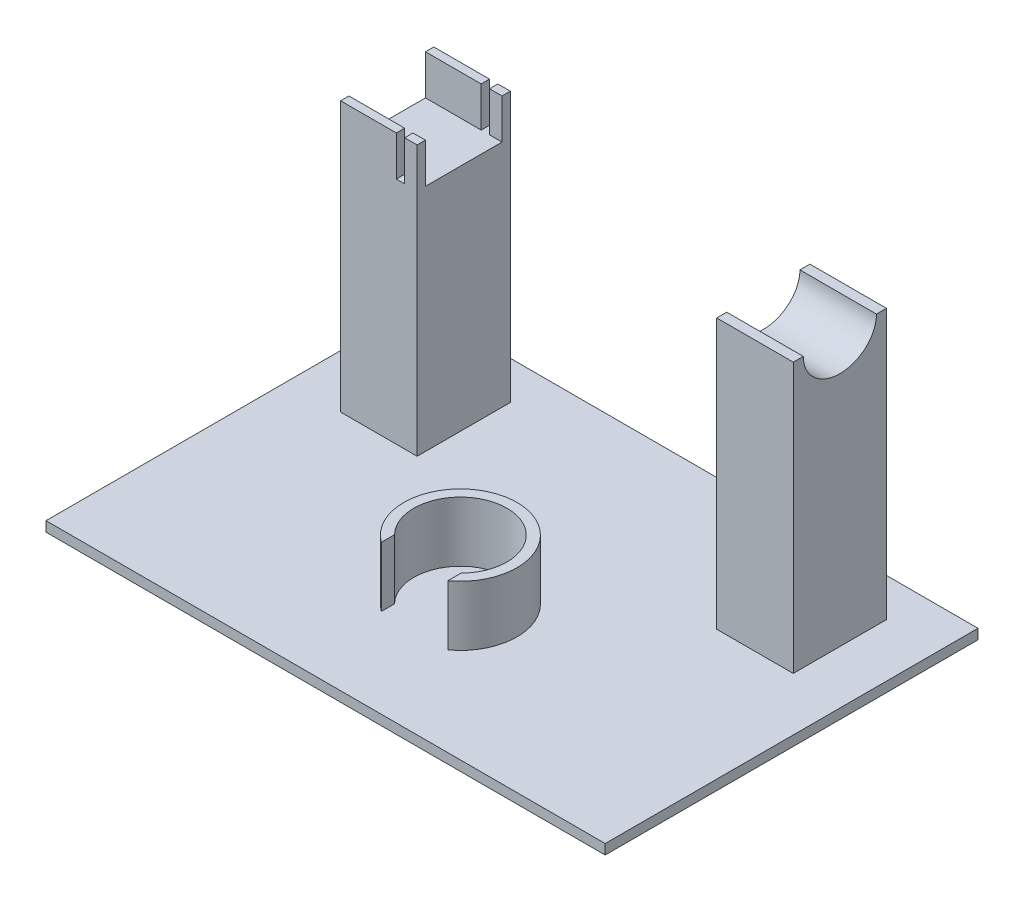
SolidWorks part; units mm, degrees
ref_plane "Front Plane" through (0, 0, 0) normal (0, 0, 1) x (1, 0, 0)
ref_plane "Top Plane" through (0, 0, 0) normal (0, 1, 0) x (1, 0, 0)
ref_plane "Right Plane" through (0, 0, 0) normal (1, 0, 0) x (0, 0, -1)
sketch "Sketch1" plane through (0, 0, 0) normal (0, 1, 0) x (1, 0, 0)
  line L1 (-84, 56) -> (84, 56)
  line L2 (-84, 56) -> (-84, -56)
  line L3 (-84, -56) -> (84, -56)
  line L4 (84, 56) -> (84, -56)
  line L5 (-84, 56) -> (84, -56) construction
  line L6 (-84, -56) -> (84, 56) construction
  point P0 (0, 0)
  dimension "D1" = 168
  dimension "D2" = 112
extrude "Boss-Extrude1" add sketch "Sketch1" along normal blind 3 contours L2 L3 L4 L1
sketch "Sketch2" plane through (0, 3, 0) normal (0, 1, 0) x (1, 0, 0)
  line L1 (-68, 44.5) -> (68, 44.5)
  line L2 (-68, 44.5) -> (-68, -44.5)
  line L3 (-68, -44.5) -> (68, -44.5)
  line L4 (68, 44.5) -> (68, -44.5)
  line L5 (-68, 44.5) -> (68, -44.5) construction
  line L6 (-68, -44.5) -> (68, 44.5) construction
  line L8 (-68, 44.5) -> (-45, 44.5)
  line L9 (-68, 44.5) -> (-68, 16.5)
  line L10 (-68, 16.5) -> (-45, 16.5)
  line L11 (-45, 44.5) -> (-45, 16.5)
  point P0 (0, 0)
  dimension "D1" = 136
  dimension "D2" = 89
  dimension "D3" = 28
  dimension "D4" = 23
extrude "Boss-Extrude2" add sketch "Sketch2" along normal blind 81 contours L8 L11 L10 L9
mirror "Mirror1" about plane through (0, 0, 0) normal (1, 0, 0) of "Boss-Extrude2"
sketch "Sketch11" plane through (0, 84, 0) normal (0, 1, 0) x (1, 0, 0)
  line L1 (-45, 16.5) -> (-45, 44.5)
  line L4 (-73, 42) -> (-45, 42)
  line L5 (-73, 42) -> (-73, 19)
  line L6 (-73, 19) -> (-45, 19)
  line L7 (-45, 42) -> (-45, 19)
  line L8 (-73, 42) -> (-45, 19) construction
  line L9 (-73, 19) -> (-45, 42) construction
  point P4 (-59, 30.5)
  dimension "D1" = 23
  dimension "D2" = 28
extrude "Cut-Extrude4" cut sketch "Sketch11" against normal blind 12 contours L4 L7 L6 L5
sketch "Sketch13" plane through (0, 72, 0) normal (0, 1, 0) x (1, 0, 0)
  line L3 (-51.25, 47.3449) -> (-48.75, 47.3449)
  line L4 (-51.25, 47.3449) -> (-51.25, 13.6551)
  line L5 (-51.25, 13.6551) -> (-48.75, 13.6551)
  line L6 (-48.75, 47.3449) -> (-48.75, 13.6551)
  line L7 (-51.25, 47.3449) -> (-48.75, 13.6551) construction
  line L8 (-51.25, 13.6551) -> (-48.75, 47.3449) construction
  dimension "D2" = 2.5
extrude "Cut-Extrude5" cut sketch "Sketch13" along normal blind 12 contours L4 L5 L6 L3
sketch "Sketch17" plane through (45, 0, 0) normal (-1, 0, 0) x (0, 0, 1)
  line L0 (-44.5, 84) -> (-16.5, 84) construction
  ellipse E0 centre (-30.5, 84) end of major axis (-19.5, 84) minor radius 10
extrude "Cut-Extrude6" cut sketch "Sketch17" against normal blind 40
sketch "Sketch18" plane through (0, 3, 0) normal (0, 1, 0) x (1, 0, 0)
  circle A0 centre (0, -15.5) radius 17
  point P0 (0, 0)
  dimension "D4" = 34
extrude "Boss-Extrude3" add sketch "Sketch18" along normal blind 18 contours A0
sketch "Sketch19" plane through (0, 21, 0) normal (0, 1, 0) x (1, 0, 0)
  circle A0 centre (0, -15.5) radius 14
  dimension "D1" = 28
extrude "Cut-Extrude7" cut sketch "Sketch19" against normal blind 18
sketch "Sketch20" plane through (0, 21, 0) normal (0, 1, 0) x (1, 0, 0)
  line L1 (-10, -19.5961) -> (10, -19.5961)
  line L2 (-10, -19.5961) -> (-10, -45.4039)
  line L3 (-10, -45.4039) -> (10, -45.4039)
  line L4 (10, -19.5961) -> (10, -45.4039)
  line L5 (-10, -19.5961) -> (10, -45.4039) construction
  line L6 (-10, -45.4039) -> (10, -19.5961) construction
  circle A0 centre (0, -15.5) radius 17 construction
  circle A1 centre (0, -15.5) radius 17 construction
  point P0 (0, -32.5)
  dimension "D1" = 20
extrude "Cut-Extrude8" cut sketch "Sketch20" against normal blind 18
